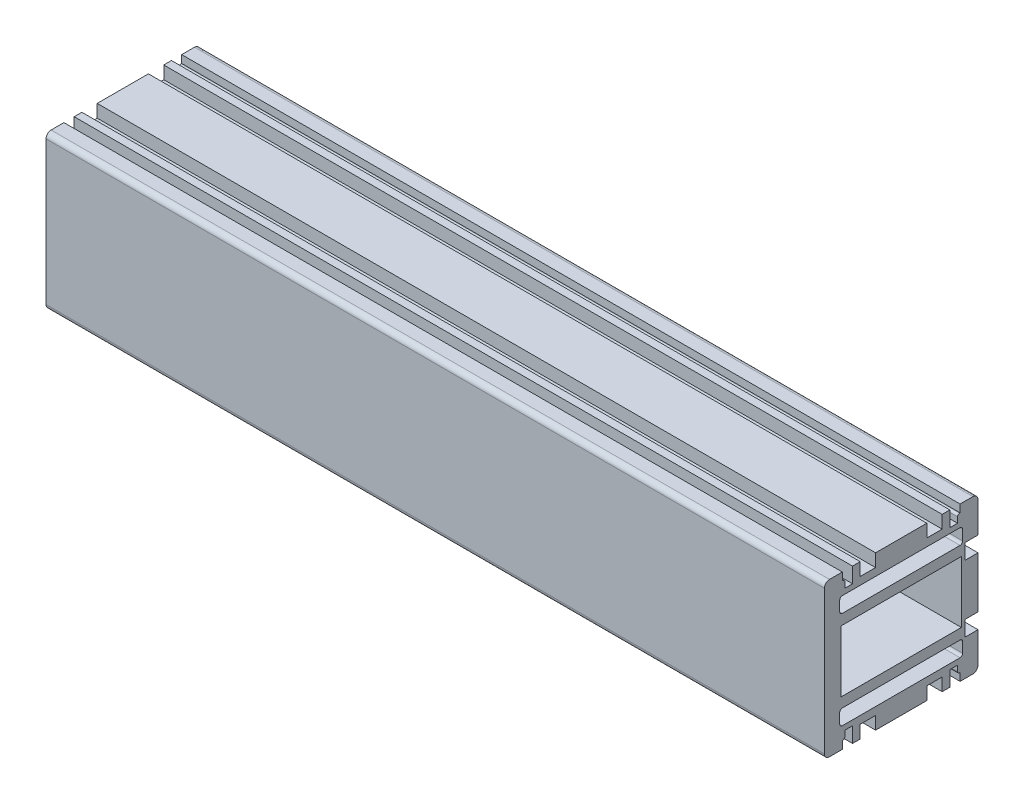
SolidWorks part; units mm, degrees
ref_plane "前视基准面" through (0, 0, 0) normal (0, 0, 1) x (1, 0, 0)
ref_plane "上视基准面" through (0, 0, 0) normal (0, 1, 0) x (1, 0, 0)
ref_plane "右视基准面" through (0, 0, 0) normal (1, 0, 0) x (0, 0, -1)
sketch "草图1" plane through (0, 0, 0) normal (1, 0, 0) x (0, 0, -1)
  line L0 (-15, 15) -> (15, -15) construction
  line L1 (-14, 15) -> (-11.5, 15)
  line L2 (-15, 14) -> (-15, -14)
  line L3 (-14, -15) -> (-11.5, -15)
  line L4 (15, 14) -> (15, 8)
  line L5 (15, 15) -> (-15, -15) construction
  line L6 (-11.5, 15) -> (-11.5, 13.5)
  line L7 (-11.5, 13.5) -> (-11.4, 13.5)
  line L8 (-11, 13.1) -> (-11, 12)
  line L9 (-11, 12) -> (-9.5, 12)
  line L10 (-9.5, 12) -> (-9.5, 15)
  line L11 (-9.5, 15) -> (-8, 15)
  line L12 (-8, 15) -> (-8, 12.5)
  line L13 (-8, 12.5) -> (-5, 12.5)
  line L14 (-5, 12.5) -> (-5, 15)
  line L15 (-5, 15) -> (5, 15)
  line L16 (0, 21.5201) -> (0, -18.309) construction
  line L17 (0, 55) -> (0, -55) construction
  line L18 (5, 12.5) -> (5, 15)
  line L19 (8, 12.5) -> (5, 12.5)
  line L20 (8, 15) -> (8, 12.5)
  line L21 (9.5, 15) -> (8, 15)
  line L22 (9.5, 12) -> (9.5, 15)
  line L23 (11, 12) -> (9.5, 12)
  line L24 (11, 13.1) -> (11, 12)
  line L25 (11.5, 13.5) -> (11.4, 13.5)
  line L26 (11.5, 15) -> (11.5, 13.5)
  line L27 (8, 15) -> (9.5, 15)
  line L28 (11.5, 15) -> (14, 15)
  line L29 (-19.8303, 0) -> (22.13, 0) construction
  line L30 (55, 0) -> (-55, 0) construction
  line L31 (8, -15) -> (9.5, -15)
  line L32 (11.5, -15) -> (11.5, -13.5)
  line L33 (11.5, -13.5) -> (11.4, -13.5)
  line L34 (11, -13.1) -> (11, -12)
  line L35 (11, -12) -> (9.5, -12)
  line L36 (9.5, -12) -> (9.5, -15)
  line L37 (9.5, -15) -> (8, -15)
  line L38 (8, -15) -> (8, -12.5)
  line L39 (8, -12.5) -> (5, -12.5)
  line L40 (5, -12.5) -> (5, -15)
  line L41 (-5, -15) -> (5, -15)
  line L42 (-5, -12.5) -> (-5, -15)
  line L43 (-8, -12.5) -> (-5, -12.5)
  line L44 (-8, -15) -> (-8, -12.5)
  line L45 (-9.5, -15) -> (-8, -15)
  line L46 (-9.5, -12) -> (-9.5, -15)
  line L47 (-11, -12) -> (-9.5, -12)
  line L48 (-11, -13.1) -> (-11, -12)
  line L49 (-11.5, -13.5) -> (-11.4, -13.5)
  line L50 (-11.5, -15) -> (-11.5, -13.5)
  line L51 (-9.5, -15) -> (-8, -15)
  line L52 (-5, -15) -> (5, -15)
  line L53 (8, -15) -> (9.5, -15)
  line L54 (11.5, -15) -> (14, -15)
  line L55 (15, 8) -> (12.5, 8)
  line L56 (12.5, 8) -> (12.5, 5)
  line L57 (12.5, 5) -> (15, 5)
  line L58 (12.5, -5) -> (15, -5)
  line L59 (12.5, -8) -> (12.5, -5)
  line L60 (15, -8) -> (12.5, -8)
  line L61 (15, 5) -> (15, -5)
  line L62 (15, -8) -> (15, -14)
  line L63 (12, -10.5) -> (12, -8.5)
  line L64 (-11.5, 11) -> (11.5, 11)
  line L65 (-12, 10.5) -> (-12, 8.5)
  line L66 (-11.5, 8) -> (11.5, 8)
  line L67 (12, 10.5) -> (12, 8.5)
  line L68 (-11.5, -8) -> (11.5, -8)
  line L69 (-12, -10.5) -> (-12, -8.5)
  line L70 (-11.5, -11) -> (11.5, -11)
  line L72 (-11.75, 6) -> (11.75, 6)
  line L73 (-11.75, 6) -> (-11.75, -6)
  line L74 (-11.75, -6) -> (11.75, -6)
  line L75 (11.75, 6) -> (11.75, -6)
  arc A0 (12, 8.5) -> (11.5, 8) centre (11.5, 8.5) cw
  arc A1 (11.5, 11) -> (12, 10.5) centre (11.5, 10.5) cw
  arc A2 (-11.5, 11) -> (-12, 10.5) centre (-11.5, 10.5) ccw
  arc A3 (-11.5, 8) -> (-12, 8.5) centre (-11.5, 8.5) cw
  arc A4 (-11, -13.1) -> (-11.4, -13.5) centre (-11.4, -13.1) cw
  arc A5 (11.4, -13.5) -> (11, -13.1) centre (11.4, -13.1) cw
  arc A6 (11.4, 13.5) -> (11, 13.1) centre (11.4, 13.1) ccw
  arc A7 (-11, 13.1) -> (-11.4, 13.5) centre (-11.4, 13.1) ccw
  arc A8 (-11.5, -8) -> (-12, -8.5) centre (-11.5, -8.5) ccw
  arc A9 (-11.5, -11) -> (-12, -10.5) centre (-11.5, -10.5) cw
  arc A10 (11.5, -11) -> (12, -10.5) centre (11.5, -10.5) ccw
  arc A11 (12, -8.5) -> (11.5, -8) centre (11.5, -8.5) ccw
  arc A12 (14, 15) -> (15, 14) centre (14, 14) cw
  arc A13 (14, -15) -> (15, -14) centre (14, -14) ccw
  arc A14 (-15, -14) -> (-14, -15) centre (-14, -14) ccw
  arc A15 (-15, 14) -> (-14, 15) centre (-14, 14) cw
  point P69 (12, 11)
  point P72 (-12, 11)
  point P77 (-11, -13.5)
  point P80 (11, -13.5)
  point P83 (11, 13.5)
  point P86 (-11, 13.5)
  point P99 (-12, -11)
  point P100 (12, -11)
  dimension "D17" = 0.5
  dimension "D18" = 0.4
  dimension "D21" = 1
  dimension "D1" = 3.5
  dimension "D2" = 1.5
  dimension "D3" = 0.5
  dimension "D4" = 1.5
  dimension "D5" = 3
  dimension "D6" = 30
  dimension "D7" = 30
  dimension "D8" = 1.5
  dimension "D9" = 2.5
  dimension "D10" = 3
  dimension "D11" = 2.5
  dimension "D12" = 7
  dimension "D13" = 3
  dimension "D14" = 4
  dimension "D15" = 3
  dimension "D16" = 24
  dimension "D19" = 23.5
  dimension "D20" = 12
extrude "凸台-拉伸1" add sketch "草图1" along normal mid plane 152 contours A15 L2 A14 L3 L50 L49 A4 L48 L47 L46 L45 L44 L43 L42 L41 L40 L39 L38 L31 L36 L35 L34 A5 L33 L32 L54 A13 L62 L60 L59 L58 L61 L57 L56 L55 L4 A12 L28 L26 L25 A6 L24 L23 L22 L21 L20 L19 L18 L15 L14 L13
hole_wizard "M6 螺纹孔1" positions "草图3" profile "草图2" tap size "M6" standard "GB"
sketch "草图3" plane through (0, 0, -15) normal (0, 0, -1) x (-1, 0, 0)
  line L0 (-76, 14) -> (-76, 8) construction
  line L1 (-76, 15) -> (76, 15) construction
  point P0 (-56, 0)
  point P1 (-41, 0)
  point P4 (41, 0)
  point P7 (56, 0)
  dimension "D1" = 20
  dimension "D2" = 15
sketch "草图2" plane through (56, 0, -15) normal (1, 0, 0) x (0, 1, 0)
  line L0 (0, 0) -> (0, 16.5022)
  line L1 (0, 16.5022) -> (2.5, 15)
  line L2 (2.5, 15) -> (2.5, 0)
  line L5 (2.5, 0) -> (0, 0)
  line L10 (0, 16.5022) -> (-2.5, 15) construction
  line L11 (0, -6.35) -> (0, 107.95) construction
  dimension "螺纹孔钻头直径" = 5
  dimension "螺纹孔钻头深度" = 15
  dimension "导头角度" = 118
cosmetic thread "孔螺蚊线1" parameters "D1"=3.25, "D2"=6
cosmetic thread "孔螺蚊线2" parameters "D1"=3.25, "D2"=6
cosmetic thread "孔螺蚊线3" parameters "D1"=3.25, "D2"=6
cosmetic thread "孔螺蚊线4" parameters "D1"=3.25, "D2"=6
hole_wizard "M6 螺纹孔2" positions "草图5" profile "草图4" tap size "M6" standard "GB"
sketch "草图5" plane through (0, -15, 0) normal (0, -1, 0) x (1, 0, 0)
  line L0 (76, 5) -> (76, -5) construction
  line L1 (76, 15) -> (-76, 15) construction
  point P0 (56, 0)
  point P1 (41, 0)
  point P4 (-41, 0)
  point P7 (-56, 0)
  dimension "D1" = 20
  dimension "D2" = 15
sketch "草图4" plane through (56, -15, 0) normal (1, 0, 0) x (0, 0, -1)
  line L0 (0, 0) -> (0, 16.5022)
  line L1 (0, 16.5022) -> (2.5, 15)
  line L2 (2.5, 15) -> (2.5, 0)
  line L5 (2.5, 0) -> (0, 0)
  line L10 (0, 16.5022) -> (-2.5, 15) construction
  line L11 (0, -6.35) -> (0, 107.95) construction
  dimension "螺纹孔钻头直径" = 5
  dimension "螺纹孔钻头深度" = 15
  dimension "导头角度" = 118
cosmetic thread "孔螺蚊线5" parameters "D1"=9, "D2"=6
cosmetic thread "孔螺蚊线6" parameters "D1"=9, "D2"=6
cosmetic thread "孔螺蚊线7" parameters "D1"=9, "D2"=6
cosmetic thread "孔螺蚊线8" parameters "D1"=9, "D2"=6
